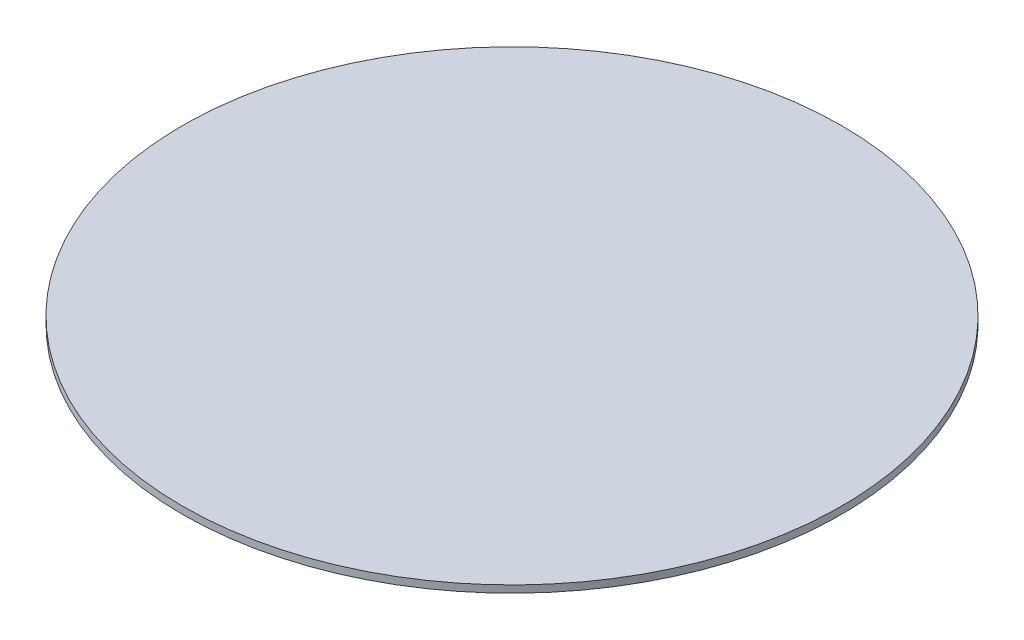
SolidWorks part; units mm, degrees
material "Glass"
ref_plane "Front Plane" through (0, 0, 0) normal (0, 0, 1) x (1, 0, 0)
ref_plane "Top Plane" through (0, 0, 0) normal (0, 1, 0) x (1, 0, 0)
ref_plane "Right Plane" through (0, 0, 0) normal (1, 0, 0) x (0, 0, -1)
sketch "Sketch1" plane through (0, 0, 0) normal (0, 1, 0) x (1, 0, 0)
  circle A0 centre (0, 0) radius 23
  dimension "D1" = 46
extrude "Boss-Extrude1" add sketch "Sketch1" along normal blind 0.5
